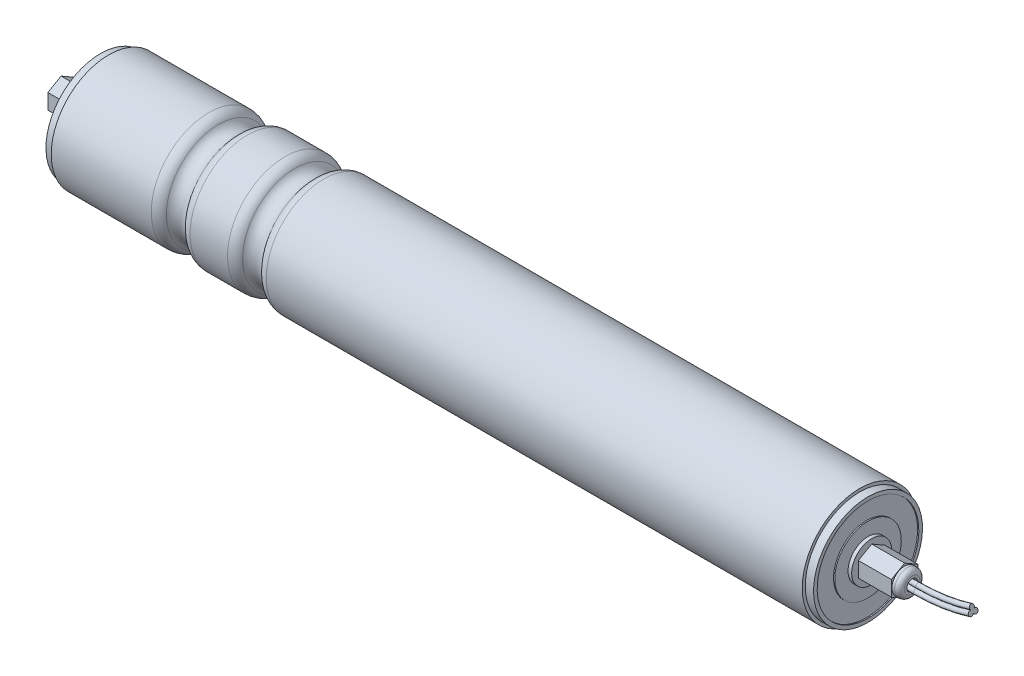
SolidWorks part; units mm, degrees
ref_plane "Front Plane" through (0, 0, 0) normal (0, 0, 1) x (1, 0, 0)
ref_plane "Top Plane" through (0, 0, 0) normal (0, 1, 0) x (1, 0, 0)
ref_plane "Right Plane" through (0, 0, 0) normal (1, 0, 0) x (0, 0, -1)
sketch "Sketch1" plane through (0, 0, 0) normal (0, 0, 1) x (1, 0, 0)
  line L0 (-162.607, 0) -> (162.607, 0) construction
  line L1 (-162.607, 0) -> (-177.593, 0) construction
  line L2 (162.607, 0) -> (179.625, 0) construction
  line L3 (-165.1, 0) -> (-162.607, 0) construction
  line L4 (162.607, 0) -> (165.1, 0) construction
  point P2 (-165.1, 0)
  point P6 (165.1, 0)
  point P7 (-157.607, 0)
  point P8 (157.607, 0)
  dimension "D1" = 17.018
  dimension "D2" = 14.986
  dimension "D3" = 5
  dimension "D4" = 5
  dimension "BF" = 330.2
  dimension "D5" = 315.214
sketch "Sketch2" plane through (0, 0, 0) normal (0, 0, 1) x (1, 0, 0)
  line L0 (-162.607, 0) -> (-162.607, 8.382)
  line L1 (-162.607, 8.382) -> (-161.083, 8.382)
  line L2 (-161.083, 8.382) -> (-161.083, 13.97)
  line L3 (-161.083, 13.97) -> (-160.575, 13.97)
  line L4 (-160.575, 13.97) -> (-160.575, 21.336)
  line L5 (-160.575, 21.336) -> (-161.083, 21.336)
  line L6 (-161.083, 21.336) -> (-161.083, 22.86)
  line L7 (-161.083, 22.86) -> (-157.607, 22.86)
  line L8 (-157.607, 22.86) -> (-157.607, 0)
  line L9 (-162.607, 0) -> (162.607, 0) construction
  line L10 (-157.607, 0) -> (-162.607, 0)
  line L11 (-162.607, 0) -> (-177.593, 0) construction
  line L12 (0, 0) -> (0, 29.0055) construction
  line L13 (157.607, 0) -> (162.607, 0)
  line L14 (157.607, 22.86) -> (157.607, 0)
  line L15 (161.083, 22.86) -> (157.607, 22.86)
  line L16 (161.083, 21.336) -> (161.083, 22.86)
  line L17 (160.575, 21.336) -> (161.083, 21.336)
  line L18 (160.575, 13.97) -> (160.575, 21.336)
  line L19 (161.083, 13.97) -> (160.575, 13.97)
  line L20 (161.083, 8.382) -> (161.083, 13.97)
  line L21 (162.607, 8.382) -> (161.083, 8.382)
  line L22 (162.607, 0) -> (162.607, 8.382)
  dimension "D1" = 16.764
  dimension "D2" = 27.94
  dimension "D3" = 45.72
  dimension "D4" = 0.508
  dimension "D5" = 1.524
  dimension "D6" = 1.524
revolve "Revolve1" add sketch "Sketch2" angle 360 mid plane about L11
sketch "Sketch3" plane through (-162.607, 0, 0) normal (-1, 0, 0) x (0, 0, 1)
  line L1 (0, 6.4158) -> (-5.5562, 3.2079)
  line L2 (-5.5562, 3.2079) -> (-5.5562, -3.2079)
  line L3 (-5.5562, -3.2079) -> (0, -6.4158)
  line L4 (0, -6.4158) -> (5.5562, -3.2079)
  line L5 (5.5562, -3.2079) -> (5.5562, 3.2079)
  line L6 (5.5562, 3.2079) -> (0, 6.4158)
  circle A0 centre (0, 0) radius 5.5563 construction
  dimension "D1" = 11.1125
extrude "Boss-Extrude1" add sketch "Sketch3" along normal up to vertex (14.986 mm away) up to point (-177.593, 0, 0)
sketch "Sketch4" plane through (162.607, 0, 0) normal (1, 0, 0) x (0, 0, -1)
  line L6 (5.5562, 3.2079) -> (0, 6.4158)
  line L7 (5.5562, -3.2079) -> (5.5562, 3.2079)
  line L8 (0, -6.4158) -> (5.5562, -3.2079)
  line L9 (-5.5562, -3.2079) -> (0, -6.4158)
  line L10 (-5.5562, 3.2079) -> (-5.5562, -3.2079)
  line L11 (0, 6.4158) -> (-5.5562, 3.2079)
  line L12 (5.5562, 3.2079) -> (0, 6.4158)
  line L13 (5.5562, -3.2079) -> (5.5562, 3.2079)
  line L14 (0, -6.4158) -> (5.5562, -3.2079)
  line L15 (-5.5562, -3.2079) -> (0, -6.4158)
  line L16 (-5.5562, 3.2079) -> (-5.5562, -3.2079)
  line L17 (0, 6.4158) -> (-5.5562, 3.2079)
  dimension "D1" = 0
extrude "Boss-Extrude2" add sketch "Sketch4" along normal up to vertex (17.018 mm away) up to point (179.625, 0, 0)
sketch "Sketch5" plane through (179.625, 0, 0) normal (1, 0, 0) x (0, 0, -1)
  circle A0 centre (0, 0) radius 5.334
  dimension "D1" = 10.668
extrude "Cut-Extrude1" cut sketch "Sketch5" against normal blind 3.175 flip side to cut
fillet "Fillet1" radius 2.032 1 edges at (179.625, 0, -5.334)
sketch "Sketch6" plane through (0, 0, 0) normal (1, 0, 0) x (0, 0, -1)
  circle A0 centre (0, 0) radius 24.13
  dimension "D1" = 48.26
extrude "Boss-Extrude3" add sketch "Sketch6" against normal up to surface and the other way up to surface up to face at (-157.607, 22.86, 0) other way up to face at (157.607, 22.86, 0)
sketch "Sketch7" plane through (0, 0, 0) normal (0, 0, 1) x (1, 0, 0)
  line L0 (-107.489, 19.558) -> (-107.489, 24.3205) construction
  line L1 (-115.6249, 24.13) -> (-99.3531, 24.13)
  line L2 (-107.489, 19.558) -> (-75.485, 19.558) construction
  line L3 (-75.485, 19.558) -> (-75.485, 26.4003) construction
  line L4 (-91.487, 19.558) -> (-91.487, 26.4003) construction
  line L5 (157.607, 24.13) -> (-157.607, 24.13) construction
  line L6 (-67.3491, 24.13) -> (-83.6209, 24.13)
  line L7 (-162.607, 8.382) -> (-162.607, -8.382) construction
  line L8 (-165.1, 0) -> (-177.593, 0) construction
  arc A0 (-115.6249, 24.13) -> (-111.557, 21.844) centre (-115.6249, 19.3675) cw
  arc A1 (-111.557, 21.844) -> (-103.421, 21.844) centre (-107.489, 24.3205) ccw
  arc A2 (-99.3531, 24.13) -> (-103.421, 21.844) centre (-99.3531, 19.3675) ccw
  arc A3 (-83.6209, 24.13) -> (-79.553, 21.844) centre (-83.6209, 19.3675) cw
  arc A4 (-71.417, 21.844) -> (-79.553, 21.844) centre (-75.485, 24.3205) cw
  arc A5 (-67.3491, 24.13) -> (-71.417, 21.844) centre (-67.3491, 19.3675) ccw
  point P9 (-107.489, 24.13)
  dimension "D1" = 4.7625
  dimension "D2" = 32.004
  dimension "D3" = 4.572
  dimension "D4" = 55.118
revolve "Cut-Revolve1" cut sketch "Sketch7" angle 360 mid plane about L8
sketch "Sketch8" plane through (179.625, 0, 0) normal (1, 0, 0) x (0, 0, -1)
  circle A0 centre (0, 0) radius 2.286
  dimension "D1" = 4.572
extrude "Cut-Extrude2" cut sketch "Sketch8" against normal blind 5.08
sketch "Sketch9" plane through (174.545, 0, 0) normal (1, 0, 0) x (0, 0, -1)
  line L0 (0, 1.143) -> (-0.9899, -0.5715) construction
  line L1 (-0.9899, -0.5715) -> (0.9899, -0.5715) construction
  line L2 (0.9899, -0.5715) -> (0, 1.143) construction
  line L3 (0, -0.5715) -> (0, 1.143) construction
  arc A0 (-0.2967, 0.1713) -> (0.2967, 0.1713) centre (0, 1.143) ccw construction
  arc A1 (-0.6932, 0.4002) -> (0, -0.8005) centre (-0.9899, -0.5715) ccw
  arc A2 (0, -0.8005) -> (0.6932, 0.4002) centre (0.9899, -0.5715) ccw
  circle A3 centre (0, 0) radius 2.159 construction
  arc A4 (0, -0.3425) -> (-0.2967, 0.1713) centre (-0.9899, -0.5715) ccw construction
  arc A5 (0.6932, 0.4002) -> (-0.6932, 0.4002) centre (0, 1.143) ccw
  arc A6 (0.2967, 0.1713) -> (0, -0.3425) centre (0.9899, -0.5715) ccw construction
  dimension "D1" = 4.318
  dimension "D2" = 2.032
sketch "Sketch10" plane through (0, 0, 0) normal (0, 0, 1) x (1, 0, 0)
  line L0 (174.545, 0) -> (182.165, 0)
  line L1 (174.545, -2.159) -> (174.545, 2.159) construction
  arc A0 (182.165, 0) -> (205.025, 3.5098) centre (182.165, 76.2) ccw
  dimension "D1" = 76.2
  dimension "D2" = 7.62
  dimension "D3" = 22.86
sweep "Sweep1" add profiles "Sketch9" path "Sketch10"
equation "\"D4@Sketch1\" = \"D3@Sketch1\""
equation "\"D5@Sketch1\" = \"BF@Sketch1\"-.590"
